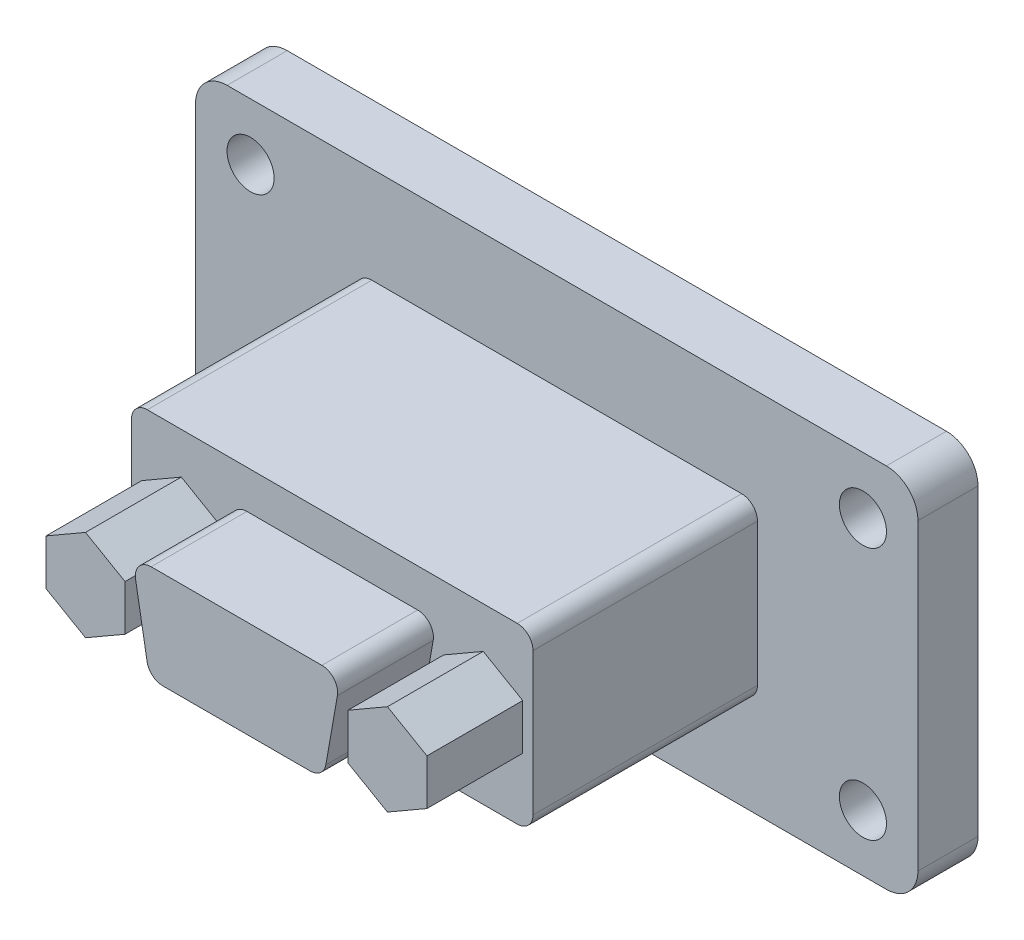
SolidWorks part; units mm, degrees
material "6061-T6 (SS)"
ref_plane "Front" through (0, 0, 0) normal (0, 0, 1) x (1, 0, 0)
ref_plane "Top" through (0, 0, 0) normal (0, 1, 0) x (1, 0, 0)
ref_plane "Right" through (0, 0, 0) normal (1, 0, 0) x (0, 0, -1)
sketch "Sketch1" plane through (0, 0, 0) normal (0, 0, 1) x (1, 0, 0)
  line L1 (-29.0195, -14.732) -> (29.0195, -14.732)
  line L2 (-29.0195, -14.732) -> (-29.0195, 14.732)
  line L3 (-29.0195, 14.732) -> (29.0195, 14.732)
  line L4 (29.0195, -14.732) -> (29.0195, 14.732)
  line L5 (-29.0195, -14.732) -> (29.0195, 14.732) construction
  line L6 (-29.0195, 14.732) -> (29.0195, -14.732) construction
  point P0 (0, 0)
  dimension "D1" = 58.039
  dimension "D2" = 29.464
extrude "Boss-Extrude1" add sketch "Sketch1" along normal blind 4.826
hole_wizard "#25 (0.1495) Diameter Hole1" positions "Sketch3" profile "Sketch2" hole size "#25" standard "ANSI Inch" end condition through all
sketch "Sketch3" plane through (0, 0, 4.826) normal (0, 0, 1) x (1, 0, 0)
  line L3 (-24.5999, 10.16) -> (24.5999, -10.16) construction
  point P0 (-24.5999, 10.16)
  point P2 (24.5999, 10.16)
  point P4 (24.5999, -10.16)
  point P6 (-24.5999, -10.16)
  dimension "D1" = 49.1998
  dimension "D4" = 20.32
sketch "Sketch2" plane through (-24.5999, 10.16, 4.826) normal (1, 0, 0) x (0, -1, 0)
  line L0 (0, 0) -> (0, 4.826)
  line L1 (0, 4.826) -> (1.8923, 4.826)
  line L2 (1.8923, 4.826) -> (1.8923, 0)
  line L5 (1.8923, 0) -> (0, 0)
  line L11 (0, -6.35) -> (0, 107.95) construction
  dimension "Thru Hole Dia." = 3.7846
  dimension "Thru Hole Depth" = 4.826
sketch "Sketch4" plane through (0, 0, 4.826) normal (0, 0, 1) x (1, 0, 0)
  line L1 (-16.129, -6.985) -> (16.129, -6.985)
  line L2 (-16.129, -6.985) -> (-16.129, 6.985)
  line L3 (-16.129, 6.985) -> (16.129, 6.985)
  line L4 (16.129, -6.985) -> (16.129, 6.985)
  line L5 (-16.129, -6.985) -> (16.129, 6.985) construction
  line L6 (-16.129, 6.985) -> (16.129, -6.985) construction
  point P0 (0, 0)
  dimension "D1" = 32.258
  dimension "D2" = 13.97
extrude "Boss-Extrude2" add sketch "Sketch4" along normal blind 18.034
fillet "Fillet1" radius 2.54 4 edges at (-29.0195, 14.732, 2.413) (-29.0195, -14.732, 2.413) (29.0195, -14.732, 2.413) (29.0195, 14.732, 2.413)
fillet "Fillet2" radius 1.27 4 edges at (-16.129, 6.985, 13.843) (-16.129, -6.985, 13.843) (16.129, -6.985, 13.843) (16.129, 6.985, 13.843)
sketch "Sketch5" plane through (0, 0, 22.86) normal (0, 0, 1) x (1, 0, 0)
  line L1 (8.1087, 2.4211) -> (7.1771, -2.8621)
  line L3 (-6.858, 3.9116) -> (6.858, 3.9116)
  line L5 (-7.1771, -2.8621) -> (-8.1087, 2.4211)
  line L7 (5.9264, -3.9116) -> (-5.9264, -3.9116)
  arc A1 (8.1087, 2.4211) -> (6.858, 3.9116) centre (6.858, 2.6416) ccw
  arc A3 (-6.858, 3.9116) -> (-8.1087, 2.4211) centre (-6.858, 2.6416) ccw
  arc A5 (5.9264, -3.9116) -> (7.1771, -2.8621) centre (5.9264, -2.6416) ccw
  arc A7 (-7.1771, -2.8621) -> (-5.9264, -3.9116) centre (-5.9264, -2.6416) ccw
  point P14 (0, 0)
extrude "Boss-Extrude3" add sketch "Sketch5" along normal blind 7.6962 and the other way offset from surface (30.5562 mm away) 7.6962 contours L3 A1 L1 A5 L7 A7 L5 A3 other way up to face at (-22.7076, 10.16, 0)
sketch "Sketch6" plane through (0, 0, 22.86) normal (0, 0, 1) x (1, 0, 0)
  line L0 (-12.1285, 0) -> (12.1285, 0) construction
  line L1 (12.1285, -3.6662) -> (15.3035, -1.8331)
  line L2 (15.3035, -1.8331) -> (15.3035, 1.8331)
  line L3 (15.3035, 1.8331) -> (12.1285, 3.6662)
  line L4 (12.1285, 3.6662) -> (8.9535, 1.8331)
  line L5 (8.9535, 1.8331) -> (8.9535, -1.8331)
  line L6 (8.9535, -1.8331) -> (12.1285, -3.6662)
  line L7 (-12.1285, -3.6662) -> (-8.9535, -1.8331)
  line L8 (-8.9535, -1.8331) -> (-8.9535, 1.8331)
  line L9 (-8.9535, 1.8331) -> (-12.1285, 3.6662)
  line L10 (-12.1285, 3.6662) -> (-15.3035, 1.8331)
  line L11 (-15.3035, 1.8331) -> (-15.3035, -1.8331)
  line L12 (-15.3035, -1.8331) -> (-12.1285, -3.6662)
  circle A0 centre (12.1285, 0) radius 3.175 construction
  circle A1 centre (-12.1285, 0) radius 3.175 construction
  dimension "D1" = 24.257
  dimension "D2" = 6.35
extrude "Boss-Extrude4" add sketch "Sketch6" along normal up to surface and the other way up to surface up to face at (0, -0.0943, 30.5562) other way up to face at (0, -0.0943, -7.6962)
